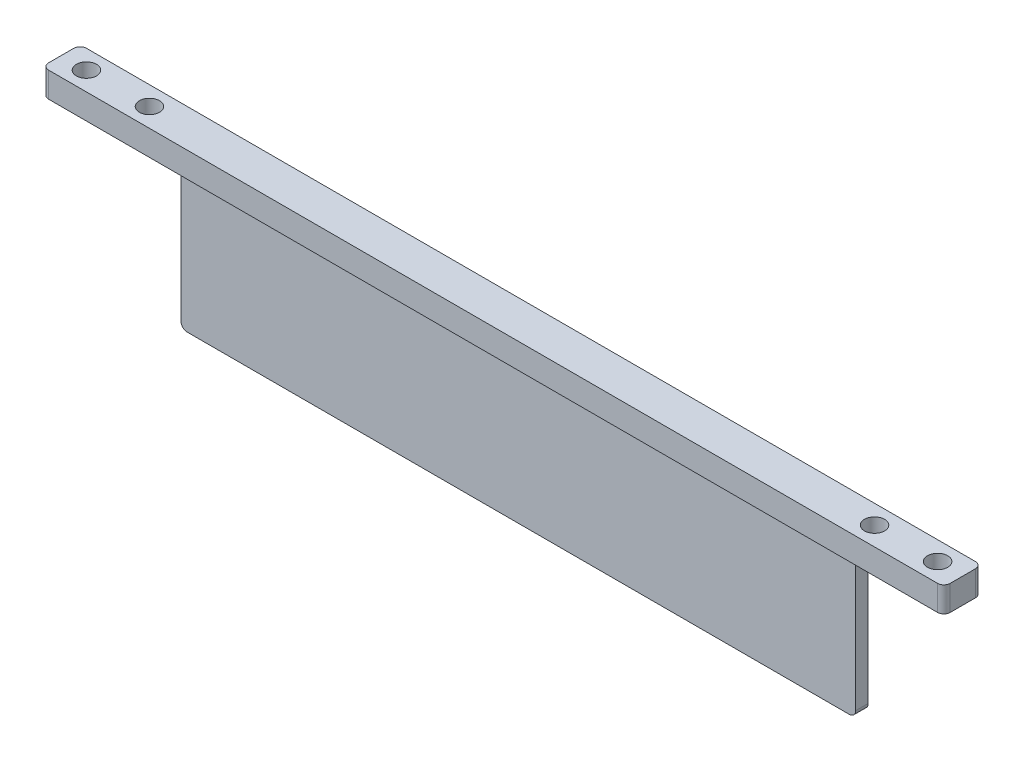
SolidWorks part; units mm, degrees
material "ABS"
ref_plane "前视基准面" through (0, 0, 0) normal (0, 0, 1) x (1, 0, 0)
ref_plane "上视基准面" through (0, 0, 0) normal (0, 1, 0) x (1, 0, 0)
ref_plane "右视基准面" through (0, 0, 0) normal (1, 0, 0) x (0, 0, -1)
other "Configuration Table"
sketch "草图1" plane through (0, 0, 0) normal (0, 1, 0) x (1, 0, 0)
  line L1 (-4, 3) -> (139, 3)
  line L2 (-4, 3) -> (-4, -3)
  line L3 (-4, -3) -> (139, -3)
  line L4 (139, 3) -> (139, -3)
  circle A0 centre (0, 0) radius 1.6
  circle A1 centre (10, 0) radius 1.6
  circle A2 centre (125, 0) radius 1.6
  circle A3 centre (135, 0) radius 1.6
  dimension "D1" = 3.2
  dimension "D2" = 10
  dimension "D3" = 115
  dimension "D4" = 10
  dimension "D5" = 3
  dimension "D6" = 6
  dimension "D7" = 4
  dimension "D8" = 4
extrude "凸台-拉伸1" add sketch "草图1" along normal blind 4
sketch "草图2" plane through (0, 0, 0) normal (0, -1, 0) x (1, 0, 0)
  line L1 (14, -3) -> (121, -3)
  line L2 (14, -3) -> (14, -1)
  line L3 (14, -1) -> (121, -1)
  line L4 (121, -3) -> (121, -1)
  line L5 (-4, -3) -> (-4, 3) construction
  line L6 (139, 3) -> (139, -3) construction
  line L7 (139, -3) -> (-4, -3) construction
  point P6 (14, -2)
  dimension "D1" = 2
  dimension "D2" = 18
  dimension "D3" = 18
extrude "凸台-拉伸2" add sketch "草图2" along normal blind 40
sketch "草图4" [suppressed] plane through (0, 0, -1) normal (0, 0, 1) x (1, 0, 0)
  line L0 (121, -40) -> (121, 0) construction
  line L1 (14, -40) -> (121, -40)
  line L2 (14, -40) -> (14, -30)
  line L3 (14, -30) -> (121, -30)
  line L4 (121, -40) -> (121, -30)
  line L5 (121, 0) -> (14, 0) construction
  dimension "D1" = 30
extrude "切除-拉伸2" [suppressed] cut sketch "草图4" against normal through all
fillet "圆角3" [suppressed] radius 1
sketch "草图3" plane through (0, 0, -1) normal (0, 0, 1) x (1, 0, 0)
  line L0 (121, -40) -> (121, 0) construction
  line L1 (14, -40) -> (121, -40)
  line L2 (14, -40) -> (14, -25)
  line L3 (14, -25) -> (121, -25)
  line L4 (121, -40) -> (121, -25)
  dimension "D1" = 15
extrude "切除-拉伸1" cut sketch "草图3" against normal through all
fillet "圆角1" [suppressed] radius 1
fillet "圆角2" radius 1 8 edges at (121, 0, -2) (121, -25, -2) (14, -25, -2) (14, 0, -2) (-4, 2, -3) (139, 2, -3) (139, 2, 3) (-4, 2, 3)
sketch "草图5" [suppressed] plane through (0, 0, -3) normal (0, 0, -1) x (-1, 0, 0)
  line L0 (-81, 4) -> (-81, -16)
  line L1 (-138, 4) -> (3, 4) construction
  line L2 (-81, -16) -> (-41, -16)
  line L3 (-41, -16) -> (-41, 4)
  line L4 (-41, 4) -> (-81, 4)
  line L5 (-121, -14) -> (-121, -1) construction
  dimension "D1" = 20
  dimension "D2" = 40
  dimension "D3" = 40
extrude "切除-拉伸3" [suppressed] cut sketch "草图5" against normal blind 10
fillet "圆角4" [suppressed] radius 1
sketch "草图6" [suppressed] plane through (0, 0, -1) normal (0, 0, 1) x (1, 0, 0)
  line L0 (27.5, -24) -> (107.5, -24) construction
  line L1 (27.5, -22) -> (107.5, -22)
  line L2 (27.5, -26) -> (107.5, -26)
  line L3 (120, -30) -> (15, -30) construction
  line L4 (27.5, -14) -> (107.5, -14) construction
  line L5 (27.5, -12) -> (107.5, -12)
  line L6 (27.5, -16) -> (107.5, -16)
  arc A0 (27.5, -22) -> (27.5, -26) centre (27.5, -24) ccw
  arc A1 (107.5, -26) -> (107.5, -22) centre (107.5, -24) ccw
  arc A2 (27.5, -12) -> (27.5, -16) centre (27.5, -14) ccw
  arc A3 (107.5, -16) -> (107.5, -12) centre (107.5, -14) ccw
  point P2 (67.5, -24)
  point P10 (67.5, -30)
  point P14 (67.5, -14)
  dimension "D1" = 2
  dimension "D2" = 6
  dimension "D3" = 80
  dimension "D5" = 10
  dimension "D4" = 2
extrude "切除-拉伸4" [suppressed] cut sketch "草图6" against normal blind 10
sketch "草图7" [suppressed] plane through (0, 0, -3) normal (0, 0, -1) x (-1, 0, 0)
  line L0 (-130.9223, -15) -> (2.2645, -15)
  line L1 (2.2645, -15) -> (2.2645, -43.7446)
  line L2 (2.2645, -43.7446) -> (-130.9223, -43.7446)
  line L3 (-130.9223, -43.7446) -> (-130.9223, -15)
  line L4 (-139, 0) -> (-121, 0) construction
  dimension "D1" = 15
extrude "切除-拉伸5" [suppressed] cut sketch "草图7" against normal blind 10
fillet "圆角5" [suppressed] radius 1
